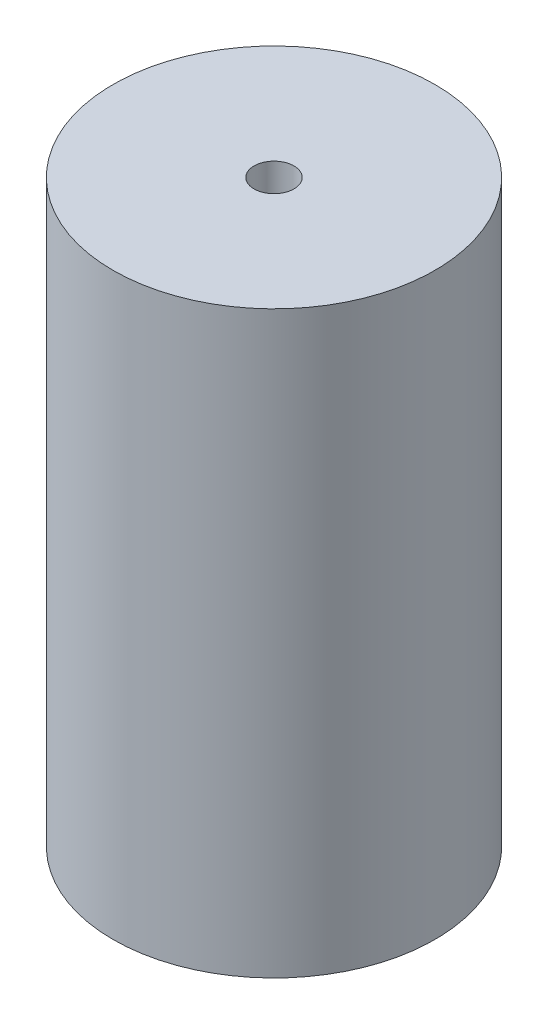
SolidWorks part; units mm, degrees
ref_plane "Front Plane" through (0, 0, 0) normal (0, 0, 1) x (1, 0, 0)
ref_plane "Top Plane" through (0, 0, 0) normal (0, 1, 0) x (1, 0, 0)
ref_plane "Right Plane" through (0, 0, 0) normal (1, 0, 0) x (0, 0, -1)
sketch "Sketch5" plane through (0, 0, 0) normal (0, 1, 0) x (1, 0, 0)
  circle A0 centre (0, 0) radius 31.75
  dimension "D1" = 63.5
extrude "Boss-Extrude1" add sketch "Sketch5" along normal blind 114.3
sketch "Sketch7" plane through (0, 114.3, 0) normal (0, 1, 0) x (1, 0, 0)
  line L1 (2.7839, 2.7839) -> (-2.7839, 2.7839)
  line L2 (2.7839, 2.7839) -> (2.7839, -2.7839)
  line L3 (2.7839, -2.7839) -> (-2.7839, -2.7839)
  line L4 (-2.7839, 2.7839) -> (-2.7839, -2.7839)
  line L5 (2.7839, 2.7839) -> (-2.7839, -2.7839) construction
  line L6 (2.7839, -2.7839) -> (-2.7839, 2.7839) construction
  circle A0 centre (0, 0) radius 3.937
  point P0 (0, 0)
  dimension "D1" = 7.874
extrude "Cut-Extrude1" cut sketch "Sketch7" against normal blind 88.9 contours A0
